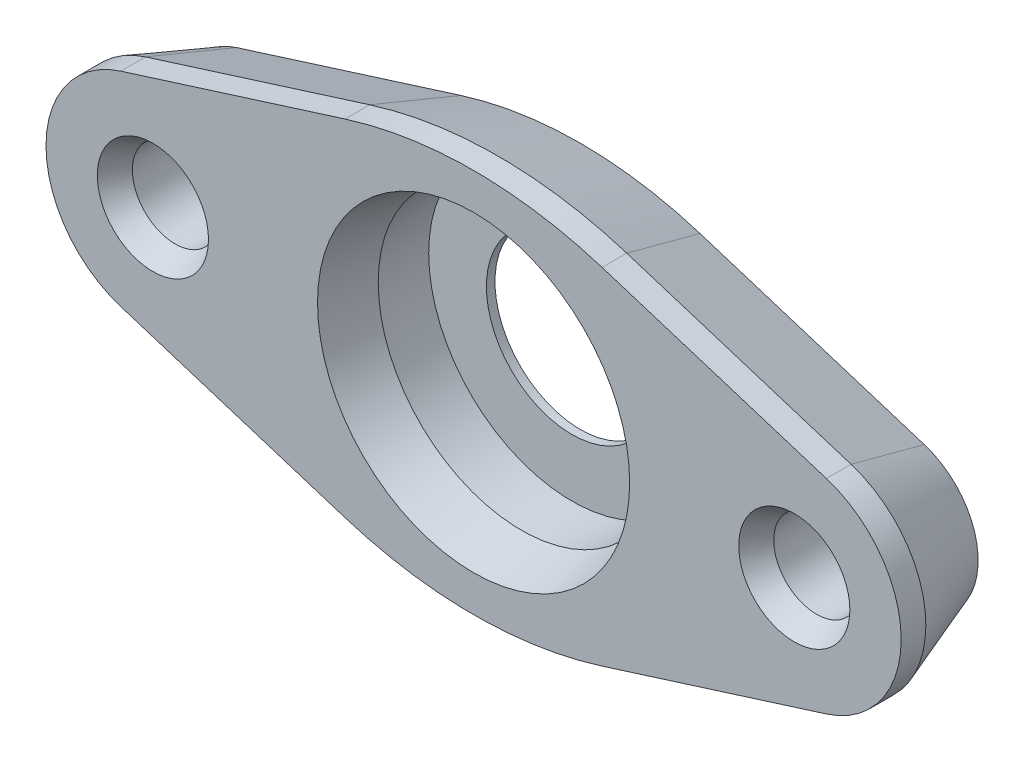
SolidWorks part; units mm, degrees
ref_plane "Front Plane" through (0, 0, 0) normal (0, 0, 1) x (1, 0, 0)
ref_plane "Top Plane" through (0, 0, 0) normal (0, 1, 0) x (1, 0, 0)
ref_plane "Right Plane" through (0, 0, 0) normal (1, 0, 0) x (0, 0, -1)
sketch "Sketch1" plane through (0, 0, 0) normal (0, 0, 1) x (1, 0, 0)
  line L0 (-8.2514, 2.3844) -> (-3.0058, 4.0376)
  line L1 (3.0058, 4.0376) -> (8.2514, 2.3844)
  line L2 (-8.2514, -2.3844) -> (-3.0058, -4.0376)
  line L3 (3.0058, -4.0376) -> (8.2514, -2.3844)
  line L4 (0, 9.0509) -> (0, -9.0509) construction
  line L5 (-11.5511, 0) -> (12.1784, 0) construction
  circle A0 centre (0, 0) radius 3.25 construction
  circle A1 centre (7.5, 0) radius 1
  circle A2 centre (-7.5, 0) radius 1
  arc A3 (-8.2514, 2.3844) -> (-8.2514, -2.3844) centre (-7.5, 0) ccw
  arc A4 (8.2514, -2.3844) -> (8.2514, 2.3844) centre (7.5, 0) ccw
  arc A5 (-3.0058, -4.0376) -> (3.0058, -4.0376) centre (0, 5.5) ccw
  arc A6 (-3.0058, 4.0376) -> (3.0058, 4.0376) centre (0, -5.5) cw
  point P17 (0, -4.9848)
  point P22 (0, 4.9848)
  dimension "D1" = 2
  dimension "D2" = 15
  dimension "D3" = 5
  dimension "D4" = 6.5
  dimension "D5" = 10
  dimension "D6" = 5.5
extrude "Boss-Extrude1" add sketch "Sketch1" along normal blind 2.5
sketch "Sketch2" plane through (0, 0, 2.5) normal (0, 0, 1) x (1, 0, 0)
  circle A0 centre (0, 0) radius 3.35
  dimension "D1" = 6.7
extrude "Cut-Extrude1" cut sketch "Sketch2" against normal blind 2.3
chamfer "Chamfer1" distance 0.7 angle 70 8 edges at (-5.6286, 3.211, 0) (-10, 0, 0) (0, 4.5, 0) (-5.6286, -3.211, 0) (5.6286, 3.211, 0) (0, -4.5, 0) (10, 0, 0) (5.6286, -3.211, 0)
chamfer "Chamfer2" distance 0.3 angle 75 1 edges at (3.35, 0, 2.5)
chamfer "Chamfer3" distance 0.3 angle 60 2 edges at (8.5, 0, 2.5) (-6.5, 0, 2.5)
sketch "Sketch3" plane through (0, 0, 0.2) normal (0, 0, 1) x (1, 0, 0)
  circle A0 centre (0, 0) radius 2
  dimension "D1" = 4
extrude "Cut-Extrude2" cut sketch "Sketch3" against normal blind 10
